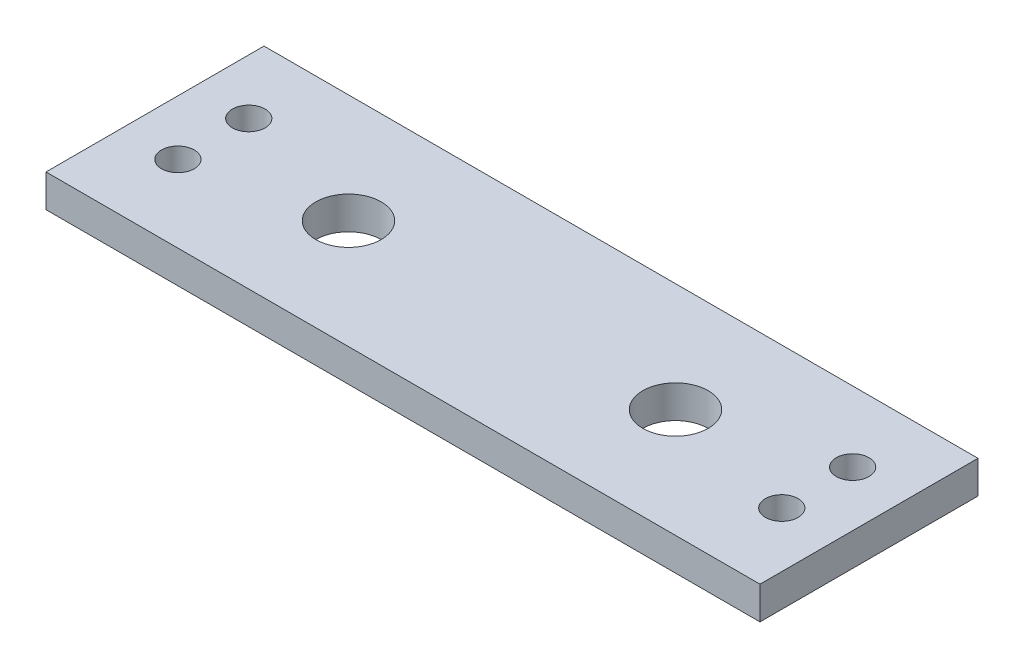
SolidWorks part; units mm, degrees
ref_plane "Płaszczyzna przednia" through (0, 0, 0) normal (0, 0, 1) x (1, 0, 0)
ref_plane "Płaszczyzna górna" through (0, 0, 0) normal (0, 1, 0) x (1, 0, 0)
ref_plane "Płaszczyzna prawa" through (0, 0, 0) normal (1, 0, 0) x (0, 0, -1)
sketch "Sketch1" plane through (0, 0, 0) normal (0, 1, 0) x (1, 0, 0)
  line L1 (0, 0) -> (65.5, 0)
  line L2 (0, 0) -> (0, 20)
  line L3 (0, 20) -> (65.5, 20)
  line L4 (65.5, 0) -> (65.5, 20)
  line L5 (0, 0) -> (65.5, 20) construction
  line L6 (0, 20) -> (65.5, 0) construction
  point P4 (32.75, 10)
  dimension "D1" = 65.5
  dimension "D2" = 20
extrude "Boss-Extrude1" add sketch "Sketch1" along normal blind 3
sketch "Sketch2" plane through (0, 3, 0) normal (0, 1, 0) x (1, 0, 0)
  line L1 (0, 20) -> (0, 0) construction
  circle A0 centre (60.45, 13.55) radius 1.5017
  circle A1 centre (60.45, 7.05) radius 1.5012
  circle A2 centre (5.05, 13.55) radius 1.5
  circle A3 centre (5.05, 7.05) radius 1.5
  circle A4 centre (47.75, 10) radius 3
  circle A5 centre (17.75, 10) radius 3
  dimension "D1" = 3
  dimension "D2" = 3
  dimension "D3" = 6
  dimension "D4" = 6
  dimension "D5" = 5.05
extrude "Cut-Extrude1" cut sketch "Sketch2" against normal blind 3
